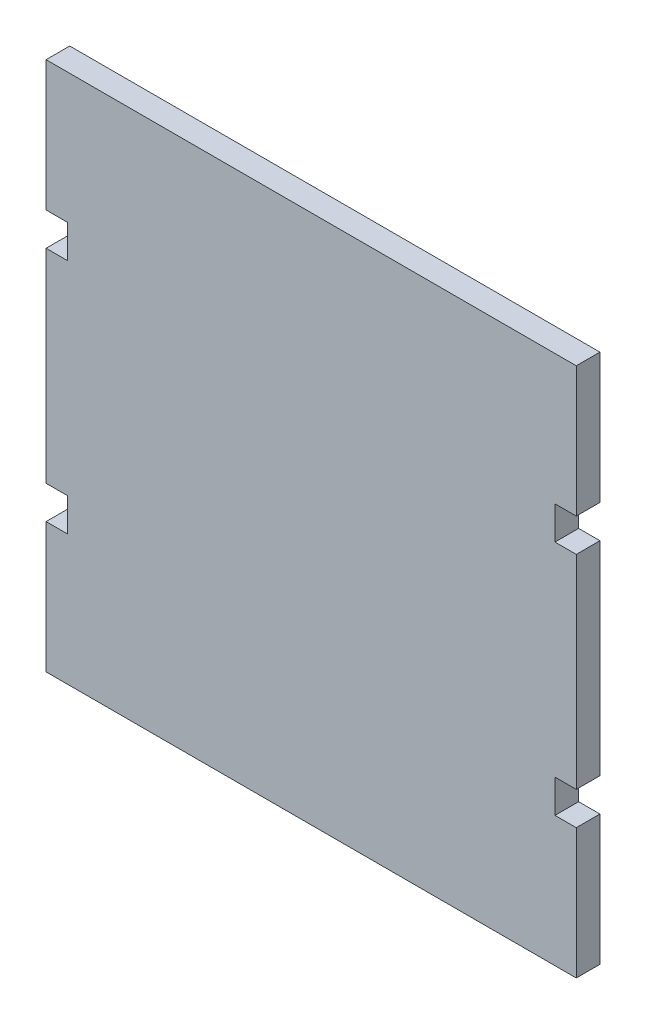
SolidWorks part; units mm, degrees
ref_plane "Plan de face" through (0, 0, 0) normal (0, 0, 1) x (1, 0, 0)
ref_plane "Plan de dessus" through (0, 0, 0) normal (0, 1, 0) x (1, 0, 0)
ref_plane "Plan de droite" through (0, 0, 0) normal (1, 0, 0) x (0, 0, -1)
sketch "Esquisse1" plane through (0, 0, 0) normal (0, 0, 1) x (1, 0, 0)
  line L0 (483.4658, -560) -> (483.4658, -285) construction
  line L1 (560, -560) -> (-560, -560)
  line L3 (560, 560) -> (-560, 560)
  line L5 (560, -560) -> (-560, 560) construction
  line L6 (560, 560) -> (-560, -560) construction
  line L7 (516.2601, 560) -> (516.2601, 267.0196) construction
  line L8 (560, -285) -> (515, -285)
  line L10 (560, -215) -> (515, -215)
  line L11 (515, -285) -> (515, -215)
  line L12 (516.2601, 267.0196) -> (516.2601, -215) construction
  line L14 (560, -285) -> (560, -560)
  line L15 (426.5098, 560) -> (426.5098, 285) construction
  line L16 (426.5098, 285) -> (560, 285) construction
  line L17 (560, 560) -> (560, 285)
  line L18 (560, 285) -> (515, 285)
  line L20 (560, 215) -> (515, 215)
  line L21 (515, 285) -> (515, 215)
  line L22 (560, 215) -> (560, -215)
  line L23 (-560, 560) -> (-560, 285)
  line L24 (-560, 285) -> (-515, 285)
  line L26 (-560, 215) -> (-515, 215)
  line L27 (-515, 285) -> (-515, 215)
  line L28 (-560, -215) -> (-515, -215)
  line L30 (-560, -285) -> (-515, -285)
  line L31 (-515, -215) -> (-515, -285)
  line L32 (-560, 215) -> (-560, -215)
  line L33 (-560, -285) -> (-560, -560)
  point P0 (0, 0)
  dimension "D1" = 1120
  dimension "D2" = 1120
  dimension "D3" = 275
  dimension "D4" = 70
  dimension "D5" = 45
  dimension "D6" = 275
  dimension "D7" = 70
  dimension "D8" = 45
  dimension "D9" = 45
  dimension "D10" = 70
extrude "Boss.-Extru.1" add sketch "Esquisse1" against normal blind 50
sketch "Esquisse2" plane through (0, 0, 0) normal (0, 0, 1) x (1, 0, 0)
  line L0 (-370, 560) -> (-370, 370) construction
  line L1 (560, 560) -> (-560, 560) construction
  line L3 (-560, 560) -> (-560, 285) construction
  circle A0 centre (-370, 370) radius 7.5
  circle A1 centre (-185, 370) radius 7.5
  circle A2 centre (0, 370) radius 7.5
  circle A3 centre (185, 370) radius 7.5
  circle A4 centre (370, 370) radius 7.5
  circle A5 centre (-185, 185) radius 7.5
  circle A6 centre (0, 185) radius 7.5
  circle A7 centre (185, 185) radius 7.5
  circle A8 centre (370, 185) radius 7.5
  circle A9 centre (-185, 0) radius 7.5
  circle A11 centre (185, 0) radius 7.5
  circle A12 centre (370, 0) radius 7.5
  circle A13 centre (-185, -185) radius 7.5
  circle A14 centre (0, -185) radius 7.5
  circle A15 centre (185, -185) radius 7.5
  circle A16 centre (370, -185) radius 7.5
  circle A17 centre (-185, -370) radius 7.5
  circle A18 centre (0, -370) radius 7.5
  circle A19 centre (185, -370) radius 7.5
  circle A20 centre (370, -370) radius 7.5
  circle A21 centre (-370, 185) radius 7.5
  circle A22 centre (-370, 0) radius 7.5
  circle A23 centre (-370, -185) radius 7.5
  circle A24 centre (-370, -370) radius 7.5
  circle A25 centre (0, 0) radius 7.5
  point P7 (0, 0)
  point P10 (0, 0)
  dimension "D2" = 15
  dimension "D1" = 190
  dimension "D3" = 190
  dimension "D4" = 5
  dimension "D5" = 5
